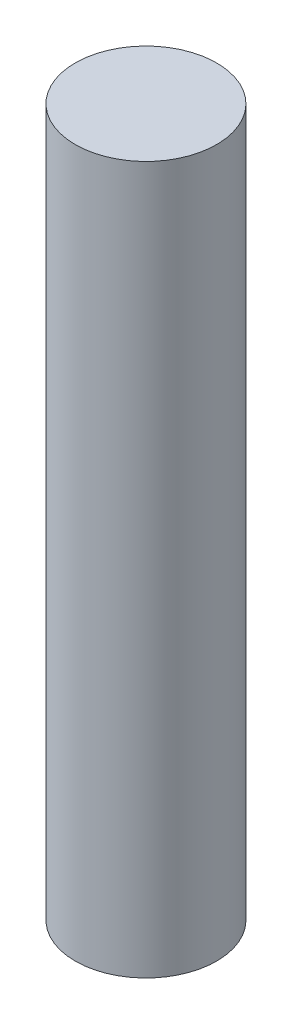
SolidWorks part; units mm, degrees
material "Alloy Steel"
ref_plane "Front Plane" through (0, 0, 0) normal (0, 0, 1) x (1, 0, 0)
ref_plane "Top Plane" through (0, 0, 0) normal (0, 1, 0) x (1, 0, 0)
ref_plane "Right Plane" through (0, 0, 0) normal (1, 0, 0) x (0, 0, -1)
sketch "Sketch1" plane through (0, 0, 0) normal (0, 1, 0) x (1, 0, 0)
  circle A0 centre (0, 0) radius 1.397
  dimension "D1" = 2.794
extrude "Boss-Extrude1" add sketch "Sketch1" along normal blind 13.97
